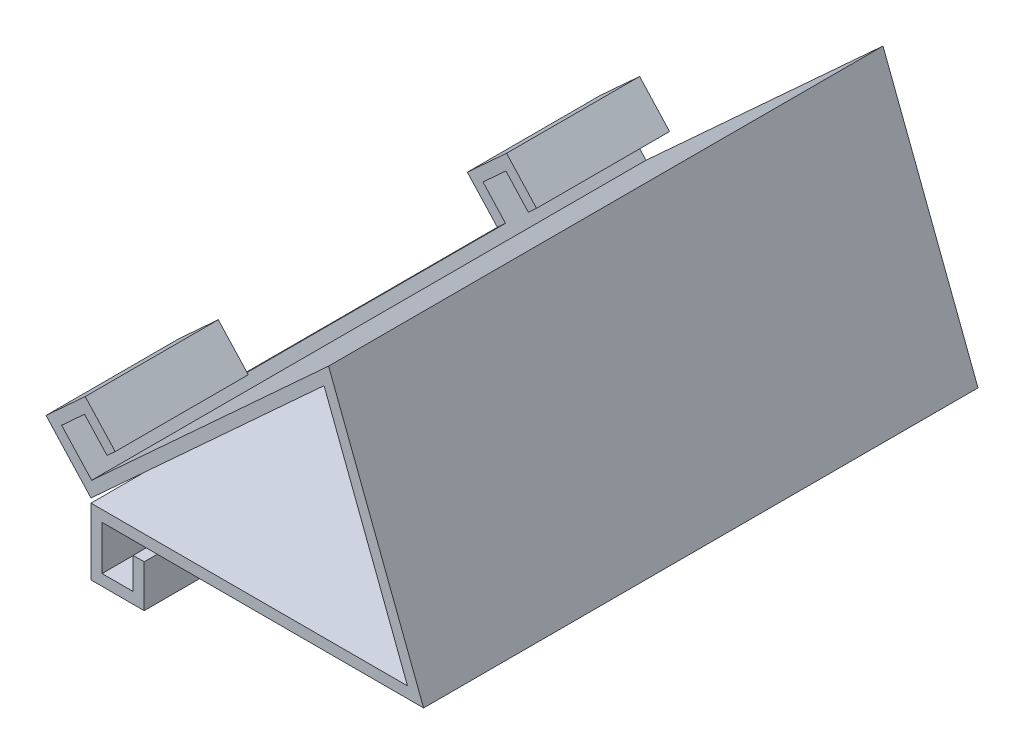
SolidWorks part; units mm, degrees
ref_plane "Front Plane" through (0, 0, 0) normal (0, 0, 1) x (1, 0, 0)
ref_plane "Top Plane" through (0, 0, 0) normal (0, 1, 0) x (1, 0, 0)
ref_plane "Right Plane" through (0, 0, 0) normal (1, 0, 0) x (0, 0, -1)
sketch "Sketch1" plane through (0, 0, 0) normal (0, 0, 1) x (1, 0, 0)
  line L0 (2.413, -2.54) -> (2.413, -0.7504)
  line L1 (2.413, -0.7504) -> (3.048, -0.7504)
  line L2 (3.048, -0.7504) -> (3.048, -3.175)
  line L3 (3.048, -3.175) -> (0, -3.175)
  line L4 (0, -55) -> (0, 55) construction
  line L5 (0, -3.175) -> (0, 0.635)
  line L7 (55, 0) -> (-55, 0) construction
  line L8 (0.635, 0) -> (0.635, -2.54)
  line L9 (0.635, -2.54) -> (2.413, -2.54)
  line L10 (0.635, 0) -> (19.05, 0)
  line L11 (19.05, 0) -> (13.6082, 14.2353)
  line L12 (13.6082, 14.2353) -> (0.0386, 1.7862)
  line L13 (0, 0.635) -> (18.1274, 0.635)
  line L14 (18.1274, 0.635) -> (13.3487, 13.1356)
  line L15 (13.3487, 13.1356) -> (0, 0.889)
  line L16 (0, 0.889) -> (-2.5757, 3.6965)
  line L17 (-2.5757, 3.6965) -> (-0.3297, 5.757)
  line L23 (-0.3297, 5.757) -> (1.3874, 3.8854)
  line L24 (1.3874, 3.8854) -> (0.9195, 3.4561)
  line L25 (0.9195, 3.4561) -> (-0.3683, 4.8598)
  line L26 (-0.3683, 4.8598) -> (-1.6785, 3.6579)
  line L27 (-1.6785, 3.6579) -> (0.0386, 1.7862)
  point P9 (0, 0)
  point P26 (0, 0)
  point P27 (0, 1.1907)
  point P28 (0, 2.1815)
  point P29 (0, 1.956)
  dimension "D1" = 1.778
  dimension "D2" = 2.54
  dimension "D3" = 3.175
  dimension "D4" = 0.635
  dimension "D5" = 0.635
  dimension "D6" = 0.635
  dimension "D7" = 0.635
  dimension "D8" = 0.635
  dimension "D9" = 19.05
  dimension "D10" = 19.05
  dimension "D11" = 0.635
  dimension "D12" = 0.635
  dimension "D13" = 1.778
  dimension "D14" = 3.81
  dimension "D15" = 2.54
  dimension "D16" = 15.24
  dimension "D17" = 0.254
  dimension "D18" = 2.54
extrude "Boss-Extrude1" add sketch "Sketch1" along normal blind 31.75
sketch "Sketch2" plane through (0.4429, 0.4063, 0) normal (-0.7369, -0.676, 0) x (0, 0, 1)
  line L0 (31.75, 4.4651) -> (0, 4.4651) construction
  line L1 (7.62, 4.4651) -> (24.13, 4.4651)
  line L2 (7.62, 4.4651) -> (7.62, 1.9251)
  line L3 (7.62, 1.9251) -> (24.13, 1.9251)
  line L4 (24.13, 4.4651) -> (24.13, 1.9251)
  line L5 (0, 4.4651) -> (0, 0.6551) construction
  line L6 (31.75, 4.4651) -> (31.75, 0.6551) construction
  dimension "D1" = 7.62
  dimension "D2" = 7.62
  dimension "D3" = 2.54
extrude "Cut-Extrude1" cut sketch "Sketch2" against normal blind 31.75
sketch "Sketch3" plane through (0, 0, 0) normal (-1, 0, 0) x (0, 0, 1)
  line L0 (31.75, -3.175) -> (0, -3.175) construction
  line L1 (24.13, -3.175) -> (7.62, -3.175)
  line L2 (24.13, -3.175) -> (24.13, -0.635)
  line L3 (24.13, -0.635) -> (7.62, -0.635)
  line L4 (7.62, -3.175) -> (7.62, -0.635)
  line L5 (0, 0.635) -> (0, -3.175) construction
  line L6 (31.75, 0.635) -> (31.75, -3.175) construction
  dimension "D1" = 7.62
  dimension "D2" = 7.62
  dimension "D3" = 2.54
extrude "Cut-Extrude2" cut sketch "Sketch3" against normal blind 31.75
